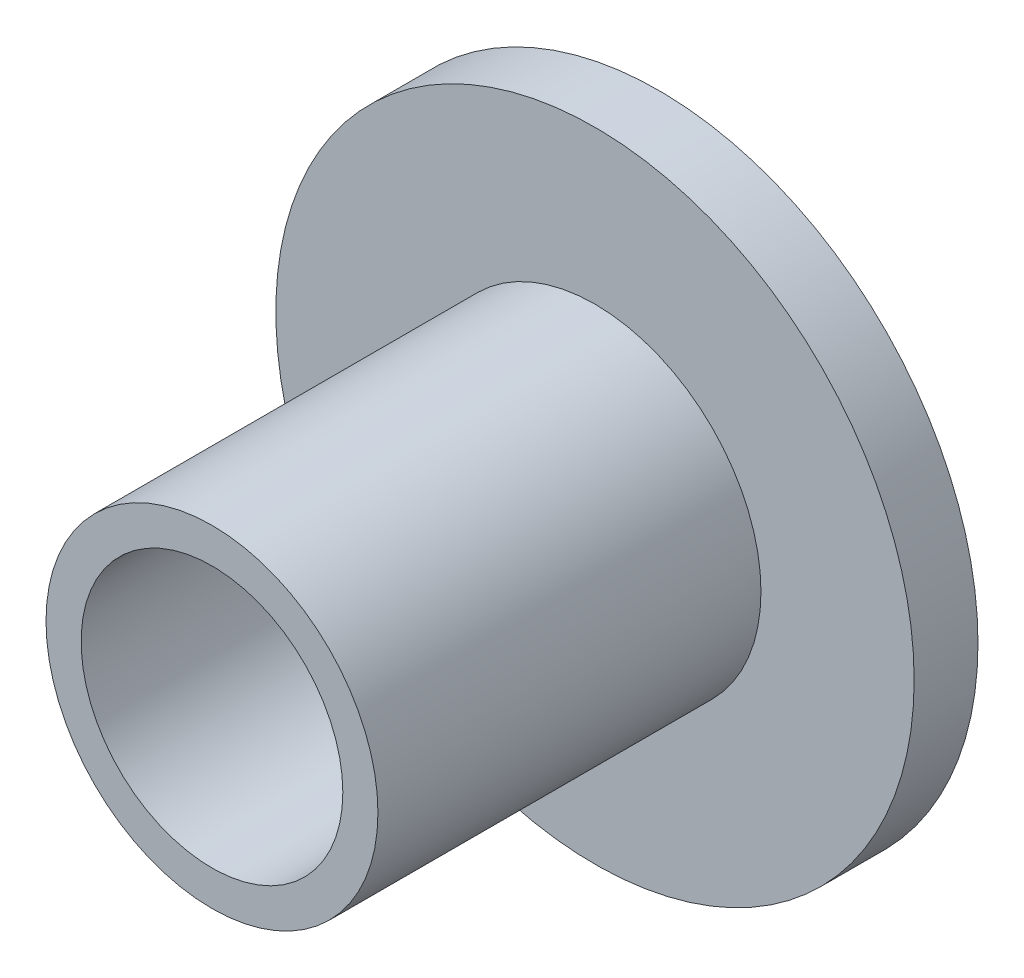
SolidWorks part; units mm, degrees
ref_plane "Plan de face" through (0, 0, 0) normal (0, 0, 1) x (1, 0, 0)
ref_plane "Plan de dessus" through (0, 0, 0) normal (0, 1, 0) x (1, 0, 0)
ref_plane "Plan de droite" through (0, 0, 0) normal (1, 0, 0) x (0, 0, -1)
sketch "Esquisse1" plane through (0, 0, 0) normal (0, 0, 1) x (1, 0, 0)
  circle A0 centre (0, 0) radius 25
  dimension "D1" = 50
extrude "Boss.-Extru.1" add sketch "Esquisse1" along normal blind 5
sketch "Esquisse2" plane through (0, 0, 5) normal (0, 0, 1) x (1, 0, 0)
  circle A0 centre (0, 0) radius 13
  circle A1 centre (0, 0) radius 10.25
  dimension "D1" = 20.5
  dimension "D2" = 26
extrude "Boss.-Extru.2" add sketch "Esquisse2" along normal blind 30
